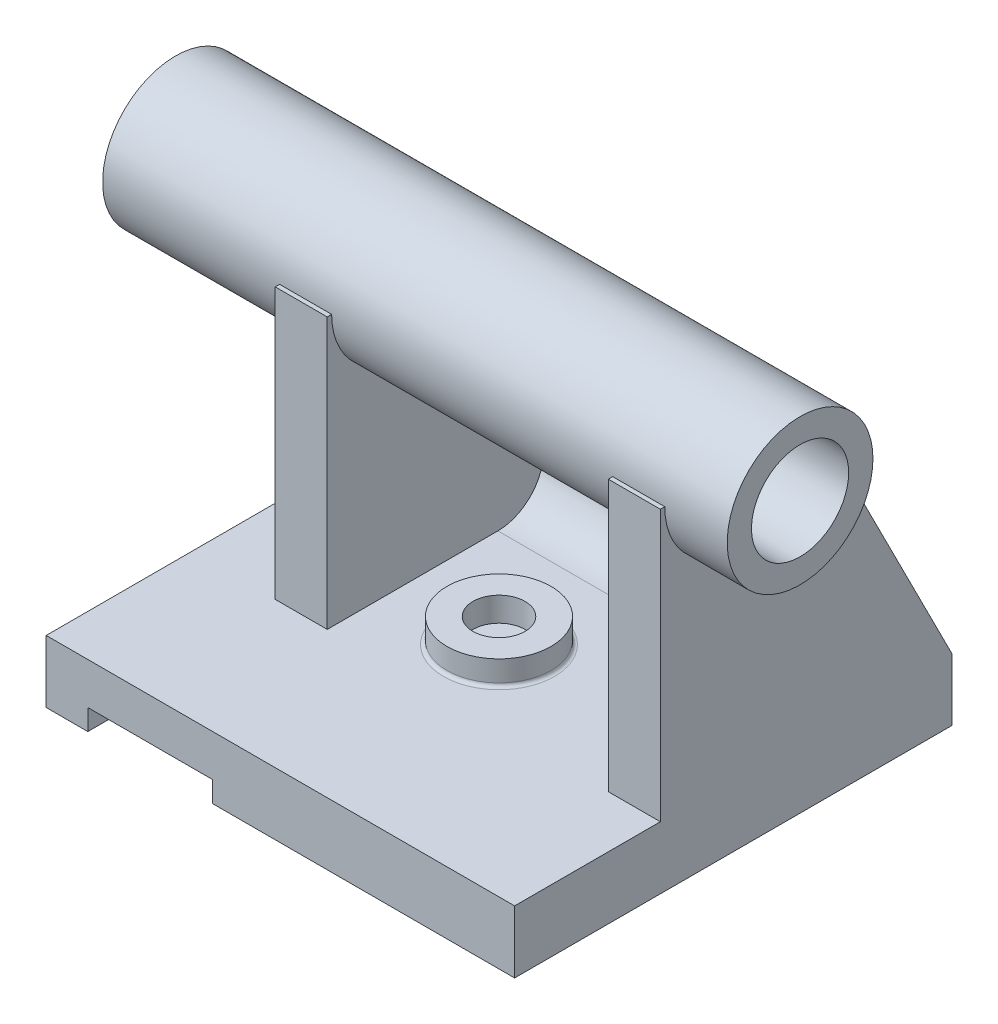
SolidWorks part; units mm, degrees
ref_plane "Front Plane" through (0, 0, 0) normal (0, 0, 1) x (1, 0, 0)
ref_plane "Top Plane" through (0, 0, 0) normal (0, 1, 0) x (1, 0, 0)
ref_plane "Right Plane" through (0, 0, 0) normal (1, 0, 0) x (0, 0, -1)
sketch "Sketch2" plane through (0, 0, 0) normal (0, 0, 1) x (1, 0, 0)
  line L0 (19.5, -9) -> (67.5, -9)
  line L1 (-67.5, 9) -> (67.5, 9)
  line L2 (-67.5, 9) -> (-67.5, -9)
  line L3 (-67.5, -9) -> (19.5, -9)
  line L4 (67.5, 9) -> (67.5, -9)
  point P0 (0, 0)
  point P11 (0, 0)
  dimension "D1" = 135
  dimension "D2" = 18
  dimension "D3" = 9
  dimension "D4" = 67.5
  dimension "D5" = 67.5
  dimension "D8" = 19.5
  dimension "D9" = 9
extrude "Boss-Extrude1" add sketch "Sketch2" against normal blind 126
sketch "Sketch4" plane through (67.5, 0, 0) normal (1, 0, 0) x (0, 0, -1)
  line L0 (42, 87) -> (42, 9)
  line L1 (42, 87) -> (86.535, 87)
  line L2 (126, 9) -> (42, 9)
  line L3 (126, 9) -> (86.535, 87)
  point P0 (126, -9)
  point P1 (126, 87)
extrude "Boss-Extrude2" add sketch "Sketch4" against normal blind 15 contours L1 L3 L2 L0
sketch "Sketch6" plane through (0, 9, 0) normal (0, 1, 0) x (1, 0, 0)
  line L0 (52.5, 126) -> (52.5, 42) construction
  line L1 (-28.5, 126) -> (-28.5, 42)
  line L2 (-28.5, 42) -> (-43.5, 42)
  line L3 (-43.5, 42) -> (-43.5, 126)
  line L4 (52.5, 126) -> (-67.5, 126) construction
  line L5 (-43.5, 126) -> (-28.5, 126)
  dimension "D2" = 15
  dimension "D1" = 81
  dimension "D3" = 84
extrude "Boss-Extrude3" add sketch "Sketch6" along normal blind 78
sketch "Sketch7" plane through (-43.5, 0, 0) normal (-1, 0, 0) x (0, 0, 1)
  line L0 (-126, 9) -> (-126, 87)
  line L1 (-126, 87) -> (-86.3552, 87)
  line L3 (-126, 9) -> (-86.3552, 87)
  line L6 (-126, 87) -> (-42, 87) construction
extrude "Cut-Extrude1" cut sketch "Sketch7" against normal blind 78
ref_plane "Plane2" through (85.5, 0, 0) normal (1, 0, 0) x (0, 0, -1)
sketch "Sketch12" plane through (85.5, 0, 0) normal (1, 0, 0) x (0, 0, -1)
  line L0 (42, 87) -> (86.535, 87) construction
  circle A0 centre (64.2675, 87) radius 21
  dimension "D1" = 42
sketch "Sketch14" plane through (0, 9, 0) normal (0, 1, 0) x (1, 0, 0)
  line L0 (-67.5, 126) -> (-67.5, 0) construction
  line L2 (67.5, 0) -> (-67.5, 0) construction
  circle A0 centre (0, 63) radius 15
  circle A1 centre (0, 63) radius 7.5
  dimension "D1" = 30
  dimension "D2" = 15
  dimension "D3" = 67.5
  dimension "D4" = 135
  dimension "D5" = 63
  dimension "D6" = 126
extrude "Boss-Extrude9" add sketch "Sketch14" along normal blind 7 contours A0 | A1
sketch "Sketch17" plane through (0, 52.7416, -103.7676) normal (0, 0.4531, -0.8915) x (-1, 0, 0)
  line L0 (-52.5, 38.3481) -> (28.5, 38.4295)
  line L1 (28.5, 38.4295) -> (28.5, -49.0674)
  line L2 (28.5, -49.0674) -> (-52.5, -49.0674)
  line L3 (-52.5, -49.0674) -> (-52.5, 38.3481)
extrude "Boss-Extrude10" add sketch "Sketch17" against normal blind 12
sketch "Sketch19" plane through (-28.5, 0, 0) normal (1, 0, 0) x (0, 0, -1)
  line L1 (112.5514, 9) -> (91.18, 9)
  line L3 (102.903, 28.0695) -> (112.5514, 9)
  line L4 (42, 87) -> (86.3552, 87) construction
  arc A0 (91.18, 9) -> (102.903, 28.0695) centre (91.18, 22.1381) ccw
  point P2 (107.7272, 18.5348)
  point P9 (75.8275, 81.5824)
  point P10 (115.2925, 3.5824)
  dimension "D1" = 26.2762
  dimension "D3" = 44.3552
  dimension "D4" = 49.18
  dimension "D5" = 58.9305
  dimension "D2" = 60.903
extrude "Boss-Extrude11" add sketch "Sketch19" along normal blind 81 contours A0 L3 L1
extrude "Boss-Extrude12" add sketch "Sketch12" against normal blind 180 contours A0
sketch "Sketch20" plane through (85.5, 0, 0) normal (1, 0, 0) x (0, 0, -1)
  circle A0 centre (64.2675, 87) radius 14
  dimension "D1" = 28
extrude "Cut-Extrude3" cut sketch "Sketch20" against normal blind 180
fillet "Fillet2" radius 1 1 edges at (0, 9, -48)
sketch "Sketch22" plane through (0, 0, 0) normal (0, 0, 1) x (1, 0, 0)
  line L1 (-67.5, 9) -> (-67.5, -9) construction
  line L2 (-55.5, -3) -> (-19.5, -3)
  line L3 (-55.5, -3) -> (-55.5, -9)
  line L4 (-55.5, -9) -> (-19.5, -9)
  line L5 (-19.5, -3) -> (-19.5, -9)
  line L6 (67.5, 9) -> (-67.5, 9) construction
  point P11 (0, 0)
  dimension "D1" = 12
  dimension "D2" = 12
  dimension "D3" = 36
  dimension "D4" = 6
extrude "Cut-Extrude4" cut sketch "Sketch22" against normal blind 180
